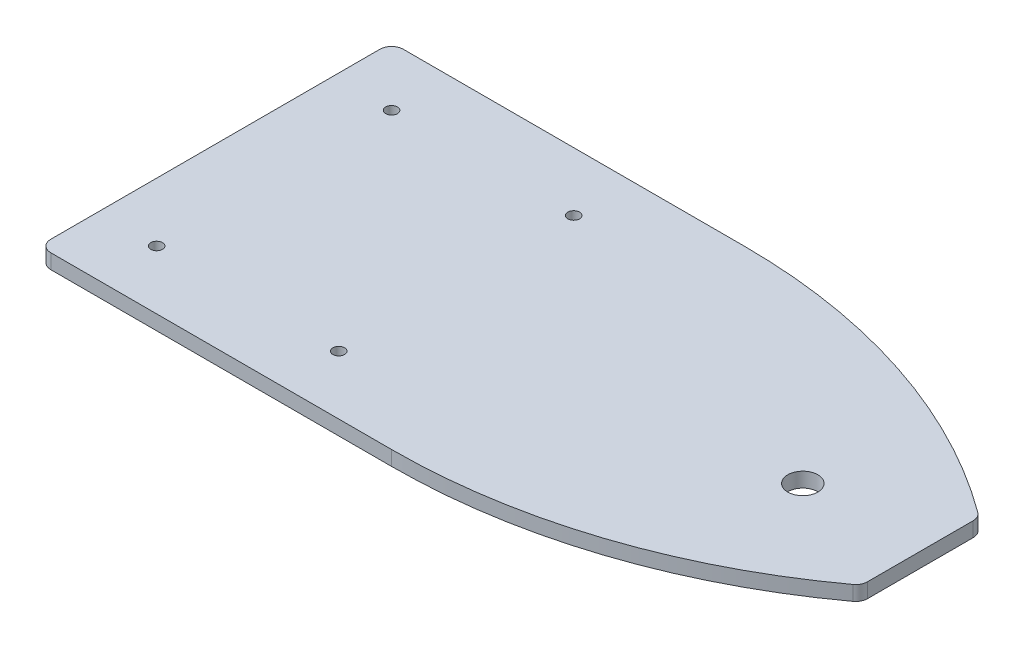
SolidWorks part; units mm, degrees
material "PLA"
ref_plane "Front" through (0, 0, 0) normal (0, 0, 1) x (1, 0, 0)
ref_plane "Top" through (0, 0, 0) normal (0, 1, 0) x (1, 0, 0)
ref_plane "Right" through (0, 0, 0) normal (1, 0, 0) x (0, 0, -1)
sketch "Sketch1" plane through (0, 0, 0) normal (0, 1, 0) x (1, 0, 0)
  line L1 (76.2, -38.1) -> (-76.2, -38.1)
  line L2 (76.2, -38.1) -> (76.2, 38.1)
  line L3 (76.2, 38.1) -> (-76.2, 38.1)
  line L4 (-76.2, -38.1) -> (-76.2, 38.1)
  line L5 (76.2, -38.1) -> (-76.2, 38.1) construction
  line L6 (76.2, 38.1) -> (-76.2, -38.1) construction
  point P0 (0, 0)
  dimension "D1" = 76.2
  dimension "D2" = 152.4
extrude "Boss-Extrude1" add sketch "Sketch1" along normal blind 3.175
sketch "Sketch4" plane through (0, 3.175, 0) normal (0, 1, 0) x (1, 0, 0)
  line L0 (0, 38.1) -> (76.2, 38.1)
  line L1 (76.2, 38.1) -> (-76.2, 38.1) construction
  line L2 (76.2, 38.1) -> (76.2, 12.7)
  line L3 (76.2, -38.1) -> (76.2, 38.1) construction
  line L4 (76.2, -38.1) -> (76.2, -12.7)
  line L5 (76.2, -38.1) -> (0, -38.1)
  line L6 (-76.2, -38.1) -> (76.2, -38.1) construction
  arc A0 (0, -38.1) -> (76.2, -12.7) centre (0, 88.9) ccw
  arc A1 (0, 38.1) -> (76.2, 12.7) centre (0, -88.9) cw
  dimension "D3" = 127
  dimension "D4" = 127
  dimension "D1" = 25.4
  dimension "D2" = 25.4
extrude "Cut-Extrude1" cut sketch "Sketch4" against normal blind 3.175
fillet "Fillet2" radius 2.54 2 edges at (76.2, 1.5875, 12.7) (76.2, 1.5875, -12.7)
fillet "Fillet3" radius 2.54 2 edges at (-76.2, 1.5875, 38.1) (-76.2, 1.5875, -38.1)
sketch "Sketch5" plane through (0, 3.175, 0) normal (0, 1, 0) x (1, 0, 0)
  line L0 (-55, 0) -> (55, 0) construction
  line L1 (76.2, -11.422) -> (76.2, 11.422) construction
  circle A0 centre (50.8, 0) radius 7.62
  dimension "D1" = 15.24
  dimension "D2" = 25.4
extrude "Cut-Extrude2" cut sketch "Sketch5" against normal blind 3.175
sketch "Sketch6" plane through (0, 3.175, 0) normal (0, 1, 0) x (1, 0, 0)
  line L0 (0, 38.1) -> (-73.66, 38.1) construction
  line L1 (-73.66, -38.1) -> (0, -38.1) construction
  line L2 (-76.2, 35.56) -> (-76.2, -35.56) construction
  circle A0 centre (-63.5, 25.4) radius 1.27
  circle A1 centre (-63.5, -25.4) radius 1.27
  circle A2 centre (-24.13, 25.4) radius 1.27
  circle A3 centre (-24.13, -25.4) radius 1.27
  dimension "D1" = 2.54
  dimension "D2" = 2.54
  dimension "D4" = 12.7
  dimension "D7" = 2.54
  dimension "D8" = 2.54
  dimension "D3" = 12.7
  dimension "D5" = 12.7
  dimension "D6" = 12.7
  dimension "D9" = 39.37
  dimension "D10" = 39.37
extrude "Cut-Extrude3" cut sketch "Sketch6" against normal blind 3.175
sketch "Sketch7" plane through (0, 0, 0) normal (0, -1, 0) x (1, 0, 0)
  circle A0 centre (50.8, 0) radius 7.62 construction
  circle A1 centre (50.8, 0) radius 7.62
  circle A2 centre (50.8, 0) radius 3.25
  circle M6 centre (50.8, 0) radius 7.62
  dimension "D1" = 6.5
extrude "Boss-Extrude2" add sketch "Sketch7" against normal up to surface (3.175 mm away) contours A2 M6 up to face at (-63.5, 3.175, 26.67)
